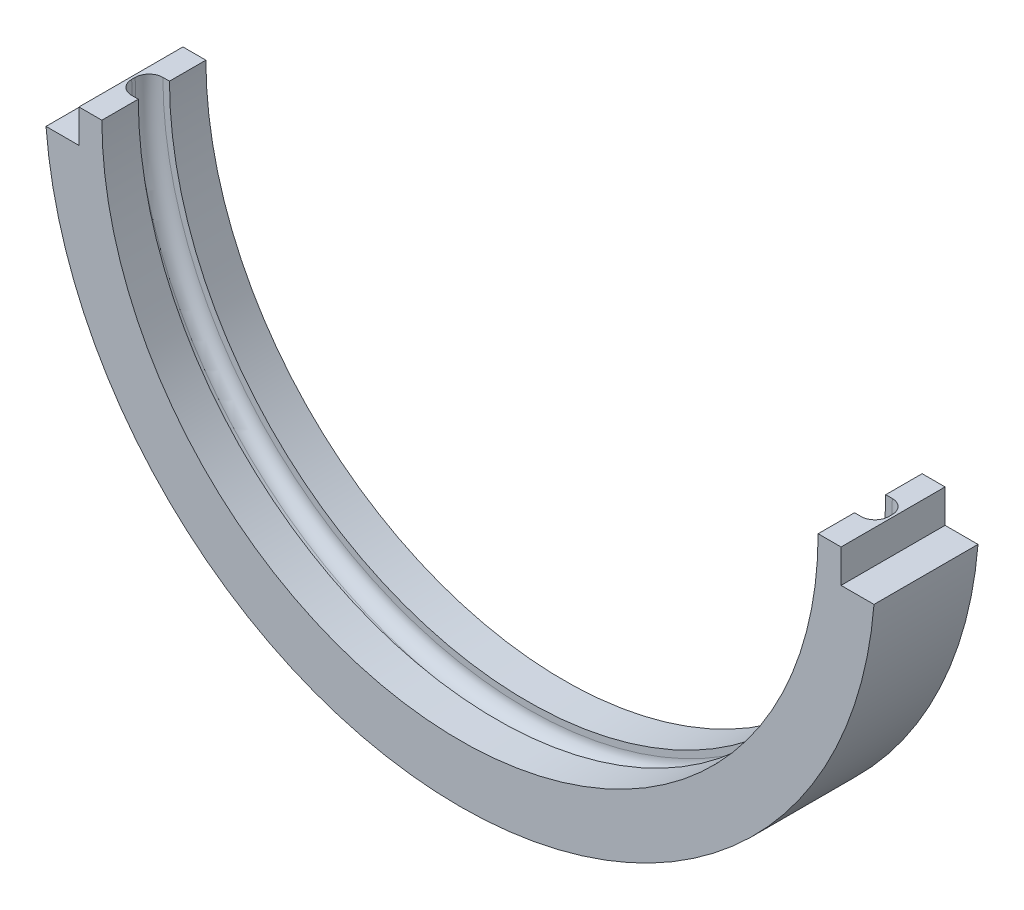
SolidWorks part; units mm, degrees
ref_plane "Front Plane" through (0, 0, 0) normal (0, 0, 1) x (1, 0, 0)
ref_plane "Top Plane" through (0, 0, 0) normal (0, 1, 0) x (1, 0, 0)
ref_plane "Right Plane" through (0, 0, 0) normal (1, 0, 0) x (0, 0, -1)
sketch "Sketch1" plane through (0, 0, 0) normal (0, 0, 1) x (1, 0, 0)
  line L0 (-69.342, 76.073) -> (-76.073, 76.073)
  line L1 (69.342, 76.073) -> (76.073, 76.073)
  circle A0 centre (0, 76.073) radius 76.073
  circle A1 centre (0, 76.073) radius 69.342
  dimension "D1" = 152.146
  dimension "D2" = 138.684
extrude "Boss-Extrude1" add sketch "Sketch1" along normal blind 5.715 contours A1 L0 A0 L1
sketch "Sketch3" plane through (0, 0, 5.715) normal (0, 0, 1) x (1, 0, 0)
  line L0 (-65.5955, 76.073) -> (-76.073, 76.073)
  line L1 (65.5955, 76.073) -> (76.073, 76.073)
  circle A0 centre (0, 76.073) radius 76.073
  circle A1 centre (0, 76.073) radius 65.5955
  arc M3 (69.342, 76.073) -> (-69.342, 76.073) centre (0, 76.073) cw
  line M4 (-69.342, 76.073) -> (-76.073, 76.073)
  arc M5 (-76.073, 76.073) -> (76.073, 76.073) centre (0, 76.073) ccw
  line M6 (76.073, 76.073) -> (69.342, 76.073)
  dimension "D1" = 131.191
extrude "Boss-Extrude2" add sketch "Sketch3" along normal blind 6.6675 contours A1 L0 L1 M3 | M6 M3 M4 M5
sketch "Sketch4" plane through (0, 0, 0) normal (0, 0, -1) x (-1, 0, 0)
  line L0 (-65.5955, 76.073) -> (-76.073, 76.073)
  line L1 (65.5955, 76.073) -> (76.073, 76.073)
  circle A0 centre (0, 76.073) radius 76.073
  circle A1 centre (0, 76.073) radius 65.5955
  arc M3 (69.342, 76.073) -> (-69.342, 76.073) centre (0, 76.073) cw
  line M4 (-69.342, 76.073) -> (-76.073, 76.073)
  arc M5 (-76.073, 76.073) -> (76.073, 76.073) centre (0, 76.073) ccw
  line M6 (76.073, 76.073) -> (69.342, 76.073)
extrude "Boss-Extrude3" add sketch "Sketch4" along normal blind 6.6675 contours A1 L0 L1 M3 | M6 M3 M4 M5
fillet "Fillet1" radius 2.54 2 edges at (0, 6.731, 0) (0, 6.731, 5.715)
sketch "Sketch5" plane through (0, 0, 0) normal (0, 1, 0) x (1, 0, 0)
  line L0 (64.2819, -2.8575) -> (-64.2819, -2.8575) construction
  circle A0 centre (0, -2.8575) radius 1.524
  dimension "D1" = 3.048
extrude "Cut-Extrude1" cut sketch "Sketch5" along normal blind 6.35
sketch "Sketch6" plane through (0, 0, 12.3825) normal (0, 0, 1) x (1, 0, 0)
  line L1 (69.7959, 76.073) -> (75.8284, 76.073)
  line L2 (69.7959, 76.073) -> (69.7959, 69.977)
  line L3 (69.7959, 69.977) -> (75.8284, 69.977)
  line L4 (75.8284, 76.073) -> (75.8284, 69.977)
  line L5 (0, 0) -> (0, 90.126) construction
  line L6 (-75.8284, 69.977) -> (-82.0776, 69.977)
  line L7 (75.8284, 76.073) -> (82.0776, 76.073)
  line L8 (75.8284, 76.073) -> (75.8284, 69.977)
  line L9 (75.8284, 69.977) -> (82.0776, 69.977)
  line L10 (82.0776, 76.073) -> (82.0776, 69.977)
  line L11 (-82.0776, 76.073) -> (-82.0776, 69.977)
  line L12 (-75.8284, 76.073) -> (-82.0776, 76.073)
  line L13 (-75.8284, 76.073) -> (-75.8284, 69.977)
  line L14 (-69.7959, 69.977) -> (-75.8284, 69.977)
  line L15 (-75.8284, 76.073) -> (-75.8284, 69.977)
  line L16 (-69.7959, 76.073) -> (-75.8284, 76.073)
  line L17 (-69.7959, 76.073) -> (-69.7959, 69.977)
  arc A1 (-76.073, 76.073) -> (76.073, 76.073) centre (0, 76.073) ccw construction
  line M11 (-65.5955, 76.073) -> (-76.073, 76.073)
  arc M12 (-76.073, 76.073) -> (76.073, 76.073) centre (0, 76.073) ccw
  line M13 (76.073, 76.073) -> (65.5955, 76.073)
  dimension "D1" = 6.096
  dimension "D2" = 6.0325
extrude "Cut-Extrude2" cut sketch "Sketch6" against normal through all contours L12 L11 L6 M12 | L17 L13 L14 M11 | L10 L7 L9 M12 | L4 L2 L3 M13
sketch "Sketch7" plane through (0, 0, 12.3825) normal (0, 0, 1) x (1, 0, 0)
  line L0 (-69.7959, 69.977) -> (-75.8284, 69.977) construction
  line L1 (-72.8121, 69.977) -> (-85.9884, 69.977)
  line L2 (-72.8121, 69.977) -> (-72.8121, 79.2871)
  line L3 (-72.8121, 79.2871) -> (-85.9884, 79.2871)
  line L4 (-85.9884, 69.977) -> (-85.9884, 79.2871)
  line L5 (0, 20.0433) -> (0, 96.673) construction
  line L6 (72.8121, 79.2871) -> (85.9884, 79.2871)
  line L7 (85.9884, 69.977) -> (85.9884, 79.2871)
  line L8 (72.8121, 69.977) -> (85.9884, 69.977)
  line L9 (72.8121, 69.977) -> (72.8121, 79.2871)
extrude "Cut-Extrude3" cut sketch "Sketch7" against normal through all contours L2 L1 L4 L3 | L6 L7 L8 L9
